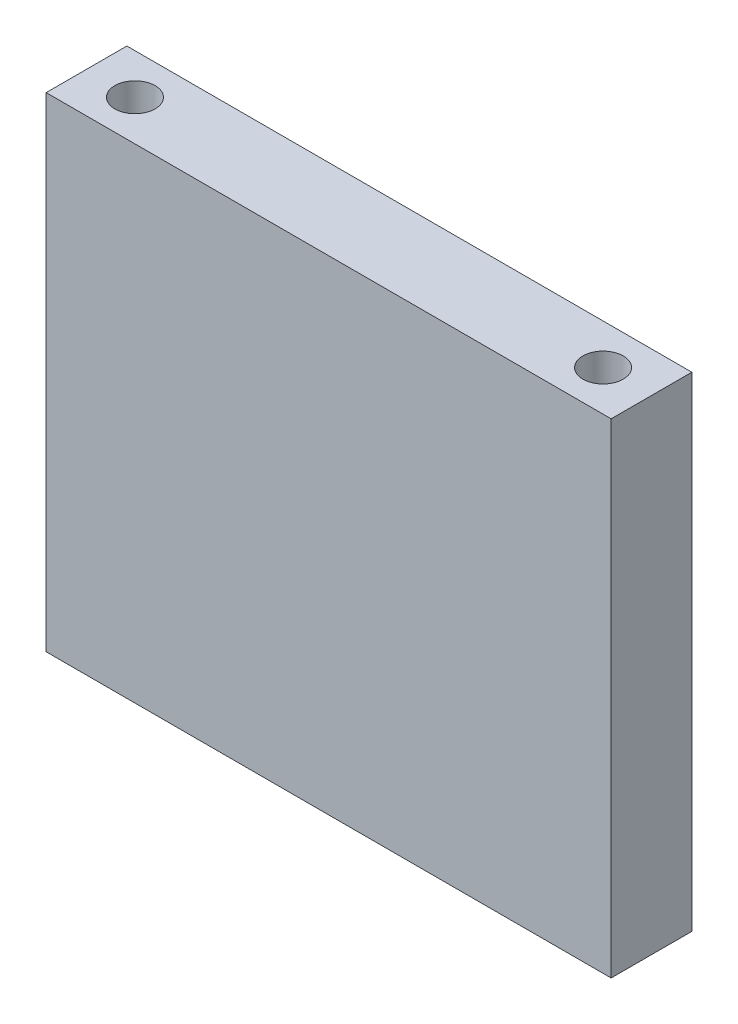
SolidWorks part; units mm, degrees
material "6061 Alloy"
ref_plane "Front Plane" through (0, 0, 0) normal (0, 0, 1) x (1, 0, 0)
ref_plane "Top Plane" through (0, 0, 0) normal (0, 1, 0) x (1, 0, 0)
ref_plane "Right Plane" through (0, 0, 0) normal (1, 0, 0) x (0, 0, -1)
sketch "Sketch1" plane through (0, 0, 0) normal (0, 0, 1) x (1, 0, 0)
  line L1 (-35, 30) -> (35, 30)
  line L2 (-35, 30) -> (-35, -30)
  line L3 (-35, -30) -> (35, -30)
  line L4 (35, 30) -> (35, -30)
  line L5 (-35, 30) -> (35, -30) construction
  line L6 (-35, -30) -> (35, 30) construction
  point P0 (0, 0)
  dimension "D1" = 60
  dimension "D2" = 70
extrude "Boss-Extrude1" add sketch "Sketch1" against normal blind 10
sketch "Sketch3" plane through (0, 30, 0) normal (0, 1, 0) x (1, 0, 0)
  line L0 (-35, 5) -> (35, 5) construction
  line L1 (-35, 10) -> (-35, 0) construction
  line L2 (35, 10) -> (35, 0) construction
  line L3 (0, 5) -> (0, -8.2181) construction
  circle A0 centre (-29, 5) radius 2.5
  circle A1 centre (29, 5) radius 2.5
  dimension "D1" = 5
  dimension "D2" = 6
extrude "Cut-Extrude1" cut sketch "Sketch3" against normal through all
